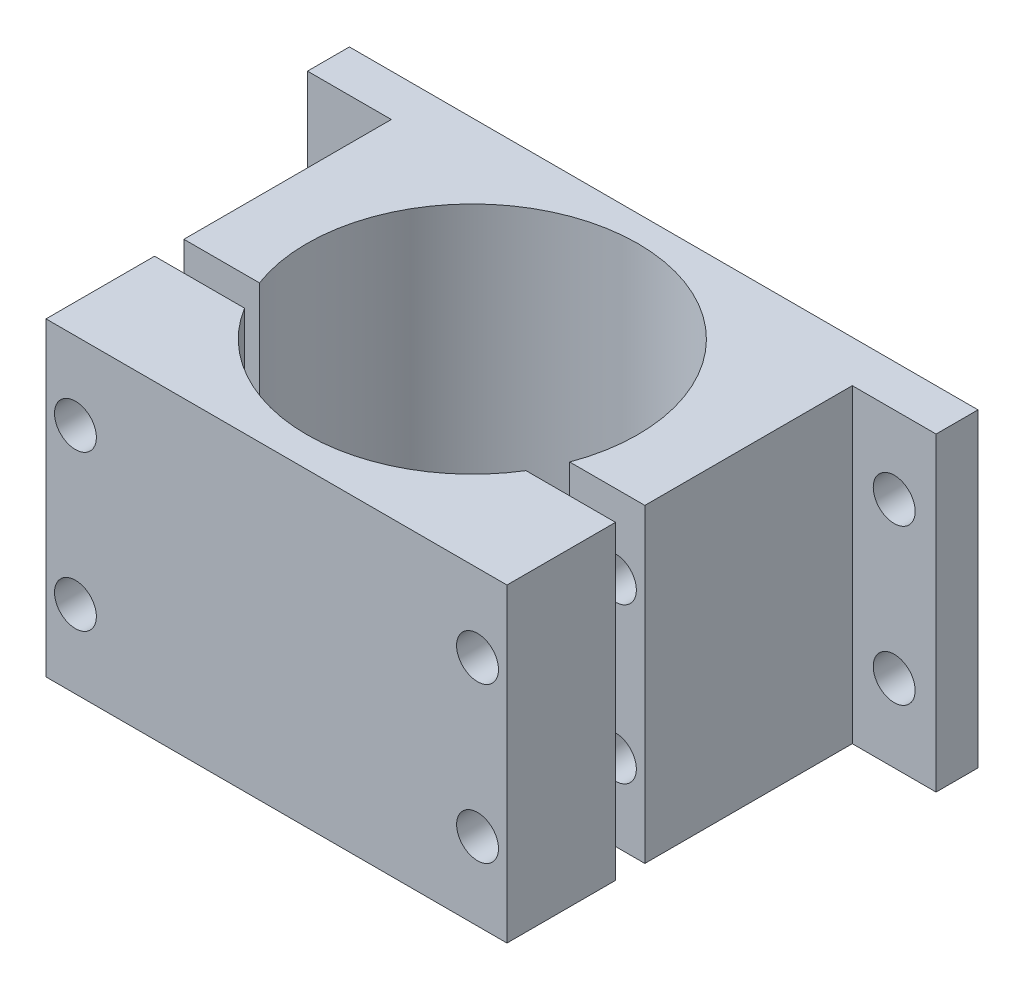
SolidWorks part; units mm, degrees
ref_plane "Front Plane" through (0, 0, 0) normal (0, 0, 1) x (1, 0, 0)
ref_plane "Top Plane" through (0, 0, 0) normal (0, 1, 0) x (1, 0, 0)
ref_plane "Right Plane" through (0, 0, 0) normal (1, 0, 0) x (0, 0, -1)
sketch "Sketch1" plane through (0, 0, 0) normal (0, 0, 1) x (1, 0, 0)
  line L1 (-37.5, -18.5) -> (37.5, -18.5)
  line L2 (-37.5, -18.5) -> (-37.5, 18.5)
  line L3 (-37.5, 18.5) -> (37.5, 18.5)
  line L4 (37.5, -18.5) -> (37.5, 18.5)
  line L5 (-37.5, -18.5) -> (37.5, 18.5) construction
  line L6 (-37.5, 18.5) -> (37.5, -18.5) construction
  point P0 (0, 0)
  point P9 (0, 18.5)
  dimension "D1" = 37
  dimension "D2" = 75
extrude "Boss-Extrude1" add sketch "Sketch1" along normal blind 5
sketch "Sketch19" plane through (0, 0, 5) normal (0, 0, 1) x (1, 0, 0)
  line L0 (-27.5, 18.5) -> (27.5, 18.5)
  line L2 (-27.5, 18.5) -> (-27.5, -18.5)
  line L4 (-27.5, -18.5) -> (27.5, -18.5)
  line L5 (27.5, -18.5) -> (27.5, 18.5)
  point P5 (0, 18.5)
  dimension "D1" = 55
extrude "Boss-Extrude5" add sketch "Sketch19" along normal blind 41.2
sketch "Sketch20" plane through (0, 18.5, 0) normal (0, 1, 0) x (1, 0, 0)
  circle A0 centre (0.0236, -22.855) radius 19.75
  dimension "D1" = 39.5
extrude "Cut-Extrude7" cut sketch "Sketch20" against normal through all
sketch "Sketch21" plane through (0, 18.5, 0) normal (0, 1, 0) x (1, 0, 0)
  line L1 (-27.5, -46.2) -> (-27.5, -5) construction
  line L2 (-27.5, -33.2481) -> (27.5, -33.2481)
  line L3 (27.5, -46.2) -> (27.5, -5) construction
sketch "Sketch22" plane through (0, 0, 46.2) normal (0, 0, 1) x (1, 0, 0)
  line L0 (-19.7264, 18.5) -> (-19.7264, -18.5)
  line L1 (-27.5, -18.5) -> (27.5, -18.5) construction
  line L2 (19.7736, 18.5) -> (19.7736, -18.5)
  circle A0 centre (-23.9882, 9.25) radius 2.4981
  circle A1 centre (-23.9882, -9.25) radius 2.4981
  circle A2 centre (23.9882, -9.25) radius 2.4981
  circle A3 centre (23.9882, 9.25) radius 2.4981
  point P19 (0, 0)
  point P26 (0, 0)
extrude "Cut-Extrude8" cut sketch "Sketch22" against normal blind 25 contours A3 | A2 | A1 | A0
split "Split1" trim tools "Sketch21" bodies to split 119 resulting bodies 120 121
sketch "Sketch23" plane through (0, 0, 5) normal (0, 0, 1) x (1, 0, 0)
  line L7 (0, 18.5) -> (0, -18.5)
  line L8 (-27.5, 18.5) -> (27.5, 18.5) construction
  line L9 (-27.5, -18.5) -> (27.5, -18.5) construction
  circle A0 centre (32.5, -9.25) radius 2.5
  circle A1 centre (32.5, 9.25) radius 2.5
  circle A2 centre (-32.5, -9.25) radius 2.5
  circle A3 centre (-32.5, 9.25) radius 2.5
extrude "Cut-Extrude9" cut sketch "Sketch23" against normal through all contours A1 | A0 | A2 | A3
sketch "Sketch24" plane through (0, 18.5, 0) normal (0, 1, 0) x (1, 0, 0)
  line L0 (-27.5, -33.2481) -> (-27.5, -29.7481)
  line L1 (-27.5, -33.2481) -> (-27.5, -5) construction
  line L2 (-27.5, -29.7481) -> (27.5, -29.7481)
  line L3 (27.5, -33.2481) -> (27.5, -5) construction
  line L4 (27.5, -29.7481) -> (27.5, -33.2481)
  line L5 (-27.5, -33.2481) -> (27.5, -33.2481)
extrude "Cut-Extrude10" cut sketch "Sketch24" against normal through all
